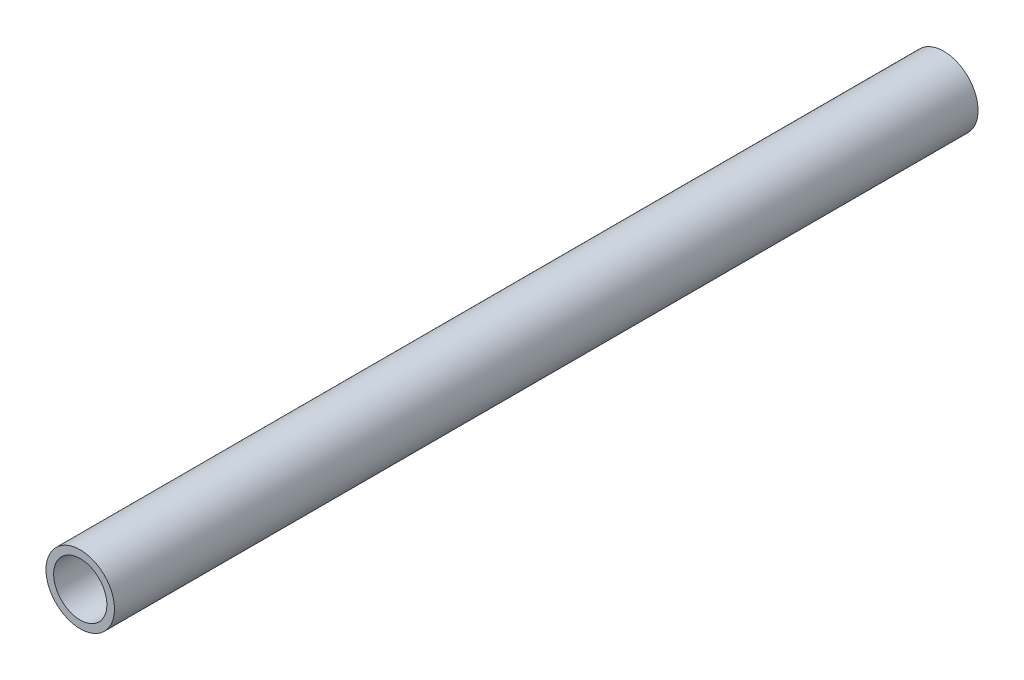
SolidWorks part; units mm, degrees
ref_plane "Front Plane" through (0, 0, 0) normal (0, 0, 1) x (1, 0, 0)
ref_plane "Top Plane" through (0, 0, 0) normal (0, 1, 0) x (1, 0, 0)
ref_plane "Right Plane" through (0, 0, 0) normal (1, 0, 0) x (0, 0, -1)
sketch "Sketch1" plane through (0, 0, 0) normal (0, 0, 1) x (1, 0, 0)
  circle A0 centre (0, 0) radius 9
  circle A1 centre (0, 0) radius 7
  dimension "D1" = 14
  dimension "D2" = 18
extrude "Boss-Extrude1" add sketch "Sketch1" along normal blind 227
